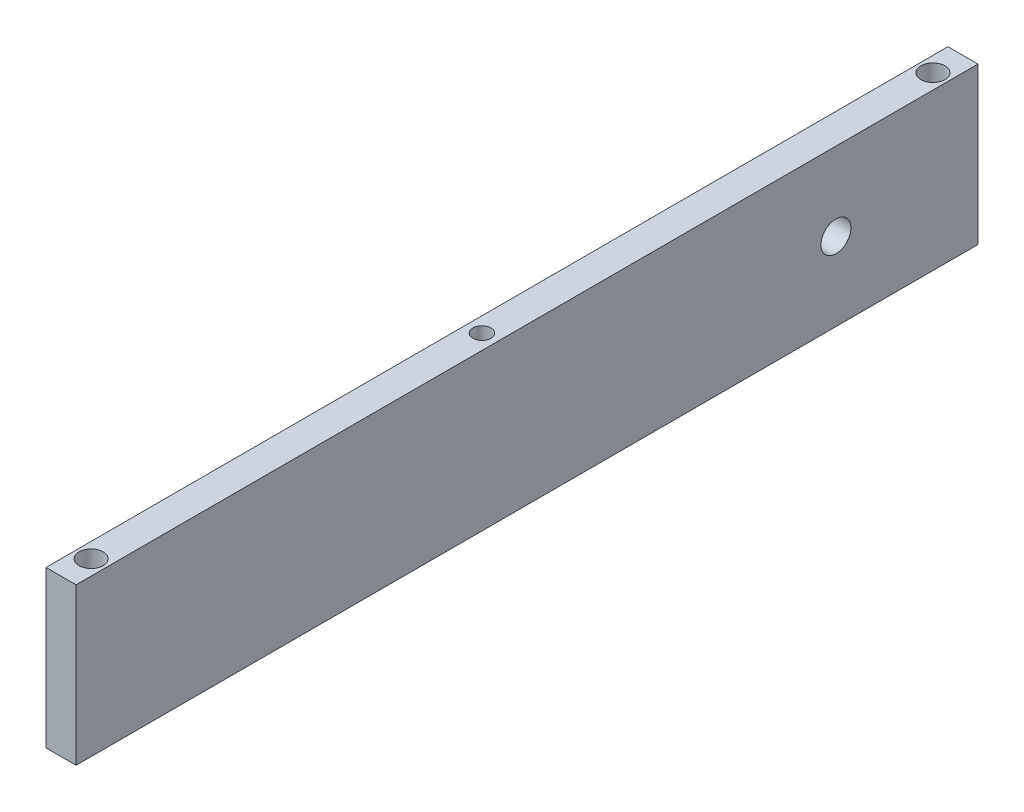
SolidWorks part; units mm, degrees
other "Markup1"
sketch "Sketch6" plane through (0, 0, 0) normal (0.7258, -0.6292, 0.2781) x (-0.261, -0.6259, -0.735)
ref_plane "Front Plane" through (0, 0, 0) normal (0, 0, 1) x (1, 0, 0)
ref_plane "Top Plane" through (0, 0, 0) normal (0, 1, 0) x (1, 0, 0)
ref_plane "Right Plane" through (0, 0, 0) normal (1, 0, 0) x (0, 0, -1)
sketch "Sketch1" plane through (0, 0, 0) normal (0, 0, 1) x (1, 0, 0)
  line L1 (-6.35, 0) -> (-6.35, 33.02)
  line L2 (-6.35, 33.02) -> (0, 33.02)
  line L3 (0, 33.02) -> (0, 0)
  line L6 (-6.35, 0) -> (0, 0)
  dimension "D3" = 6.35
  dimension "D4" = 33.02
extrude "Boss-Extrude1" add sketch "Sketch1" against normal blind 190.5
sketch "Sketch2" plane through (-6.35, 0, 0) normal (-1, 0, 0) x (0, 0, 1)
  line L0 (-190.5, 33.02) -> (-190.5, 0) construction
  circle A1 centre (-160.5, 16.51) radius 3.175
  point P4 (0, 0)
  point P5 (-190.5, 16.51)
  dimension "D1" = 6.35
  dimension "D2" = 30
extrude "Cut-Extrude1" cut sketch "Sketch2" against normal up to next
sketch "Sketch3" plane through (0, 33.02, 0) normal (0, 1, 0) x (1, 0, 0)
  line L0 (-3.175, 190.5) -> (-3.175, 0) construction
  line L1 (0, 190.5) -> (-6.35, 190.5) construction
  line L2 (0, 0) -> (-6.35, 0) construction
  circle A0 centre (-3.175, 6.35) radius 2.54
  circle A1 centre (-3.175, 184.15) radius 2.54
  circle A3 centre (-3.175, 88.9) radius 1.905
  circle A4 centre (-3.175, 88.9) radius 1.905
  dimension "D1" = 5.08
  dimension "D3" = 6.35
  dimension "D2" = 6.35
  dimension "D4" = 0
extrude "Cut-Extrude2" cut sketch "Sketch3" against normal through all
sketch "Sketch4" plane through (0, 0, 0) normal (0, -1, 0) x (1, 0, 0)
  line L0 (-9.525, 0) -> (-9.525, -381) construction
  line L1 (-12.7, 0) -> (0, 0) construction
  line L2 (-12.7, -381) -> (0, -381) construction
  line L3 (0, -381) -> (0, 0) construction
  circle A0 centre (-9.525, -374.65) radius 2.54
  circle A1 centre (-9.525, -6.35) radius 2.54
  dimension "D2" = 5.08
  dimension "D1" = 9.525
  dimension "D3" = 6.35
  dimension "D4" = 6.35
sketch "Sketch5" plane through (0, 0, -381) normal (0, 0, -1) x (-1, 0, 0)
  line L1 (6.35, 6.35) -> (0, 6.35)
  line L2 (6.35, 6.35) -> (6.35, 0)
  line L3 (6.35, 0) -> (0, 0)
  line L4 (0, 6.35) -> (0, 0)
